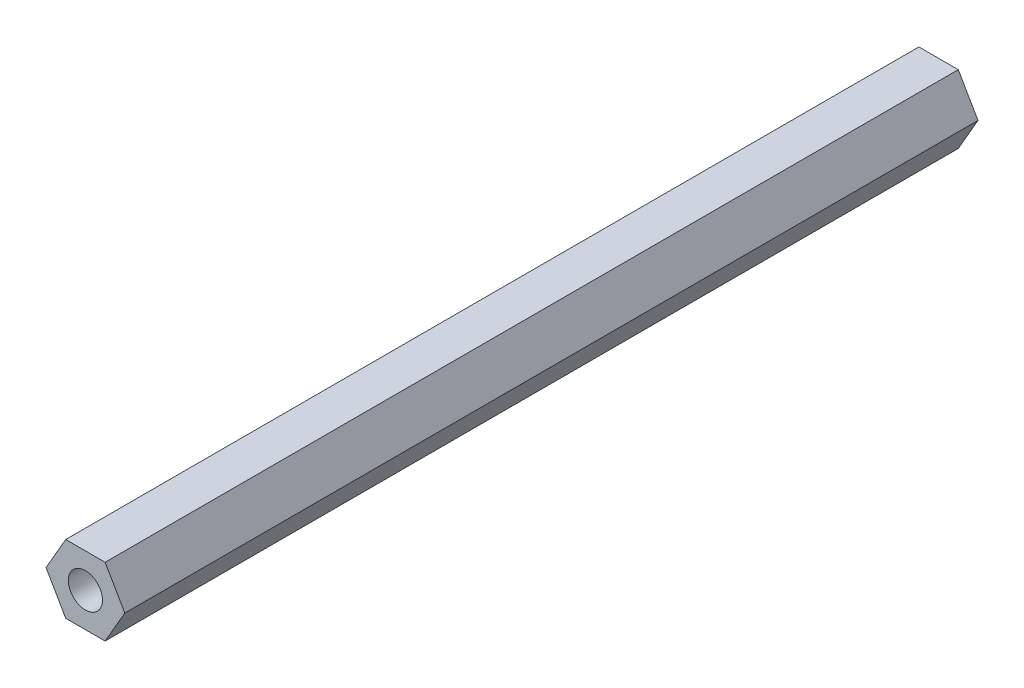
SolidWorks part; units mm, degrees
ref_plane "Front Plane" through (0, 0, 0) normal (0, 0, 1) x (1, 0, 0)
ref_plane "Top Plane" through (0, 0, 0) normal (0, 1, 0) x (1, 0, 0)
ref_plane "Right Plane" through (0, 0, 0) normal (1, 0, 0) x (0, 0, -1)
sketch "Sketch1" plane through (0, 0, 0) normal (0, 0, 1) x (1, 0, 0)
  line L1 (7.3323, 0) -> (3.6662, 6.35)
  line L2 (3.6662, 6.35) -> (-3.6662, 6.35)
  line L3 (-3.6662, 6.35) -> (-7.3323, 0)
  line L4 (-7.3323, 0) -> (-3.6662, -6.35)
  line L5 (-3.6662, -6.35) -> (3.6662, -6.35)
  line L6 (3.6662, -6.35) -> (7.3323, 0)
  circle A0 centre (0, 0) radius 6.35 construction
  dimension "D1" = 12.7
extrude "Boss-Extrude1" add sketch "Sketch1" along normal blind 158.75
sketch "Sketch2" plane through (0, 0, 158.75) normal (0, 0, 1) x (1, 0, 0)
  circle A0 centre (0, 0) radius 3.175
  dimension "D1" = 6.35
extrude "Cut-Extrude1" cut sketch "Sketch2" against normal through all both
